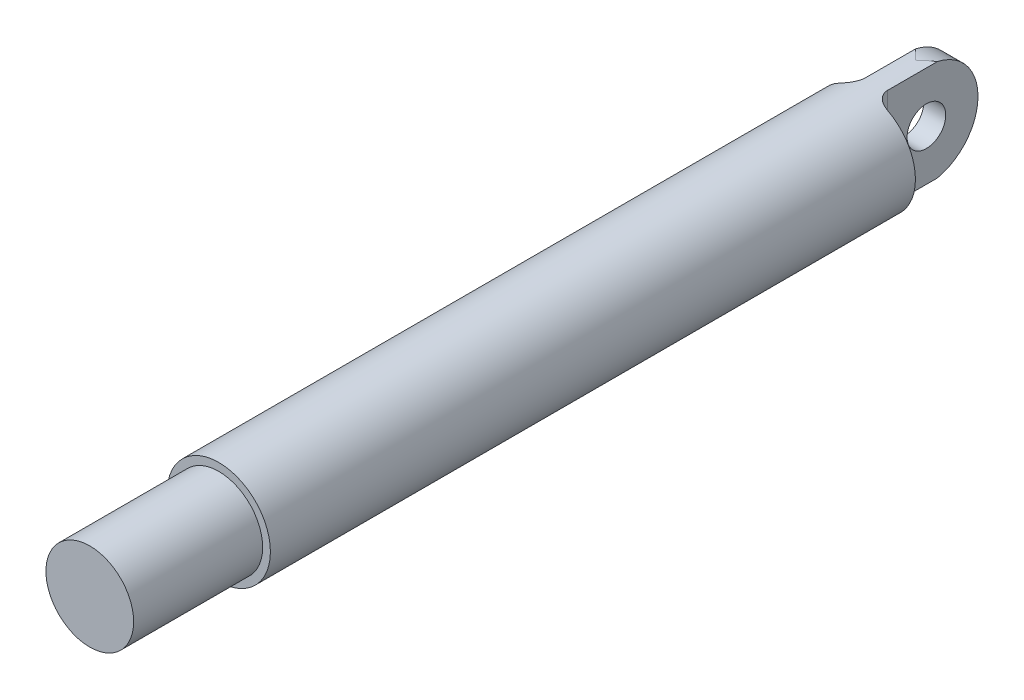
SolidWorks part; units mm, degrees
ref_plane "Front Plane" through (0, 0, 0) normal (0, 0, 1) x (1, 0, 0)
ref_plane "Top Plane" through (0, 0, 0) normal (0, 1, 0) x (1, 0, 0)
ref_plane "Right Plane" through (0, 0, 0) normal (1, 0, 0) x (0, 0, -1)
sketch "Sketch1" plane through (0, 0, 0) normal (0, 0, 1) x (1, 0, 0)
  circle A0 centre (0, 0) radius 35
  dimension "D1" = 70
ref_plane "Plane2" [suppressed] through (0, 0, -400) normal (0, 0, 1) x (1, 0, 0)
sketch "Sketch4" [suppressed] plane through (0, 0, -400) normal (0, 0, 1) x (1, 0, 0)
  circle A2 centre (0, 0) radius 35
  circle A3 centre (0, 0) radius 35 construction
loft "Loft2" [suppressed] add profiles "Sketch1", "Sketch4"
sketch "Sketch5" plane through (0, 0, 0) normal (0, 0, 1) x (1, 0, 0)
  circle A0 centre (0, 0) radius 20
  dimension "D1" = 40
extrude "Boss-Extrude4" add sketch "Sketch5" against normal blind 250
shell "Shell5" [suppressed] thickness 3
sketch "Sketch6" plane through (0, 0, 0) normal (0, 0, 1) x (1, 0, 0)
  circle A0 centre (0, 0) radius 17
  dimension "D1" = 34
extrude "Boss-Extrude5" add sketch "Sketch6" along normal blind 50
sketch "Sketch7" plane through (0, 0, 0) normal (1, 0, 0) x (0, 0, -1)
  line L0 (0, -20) -> (250, -20) construction
  line L1 (250, 20) -> (270, 20)
  line L2 (250, 20) -> (250, -20)
  line L3 (250, -20) -> (270, -20)
  arc A0 (270, -20) -> (270, 20) centre (270, 0) ccw
  circle A1 centre (270, 0) radius 7.5
  dimension "D2" = 15
  dimension "D1" = 20
extrude "Boss-Extrude6" add sketch "Sketch7" along normal mid plane 8.5
sketch "Sketch8" plane through (0, 0, -250) normal (0, 0, -1) x (-1, 0, 0)
  circle A0 centre (0, 0) radius 20
  dimension "D1" = 40
extrude "Cut-Extrude1" cut sketch "Sketch8" against normal through all both and the other way through all flip side to cut
fillet "Fillet1" radius 5 2 edges at (-4.25, 0, -250) (4.25, 0, -250)
